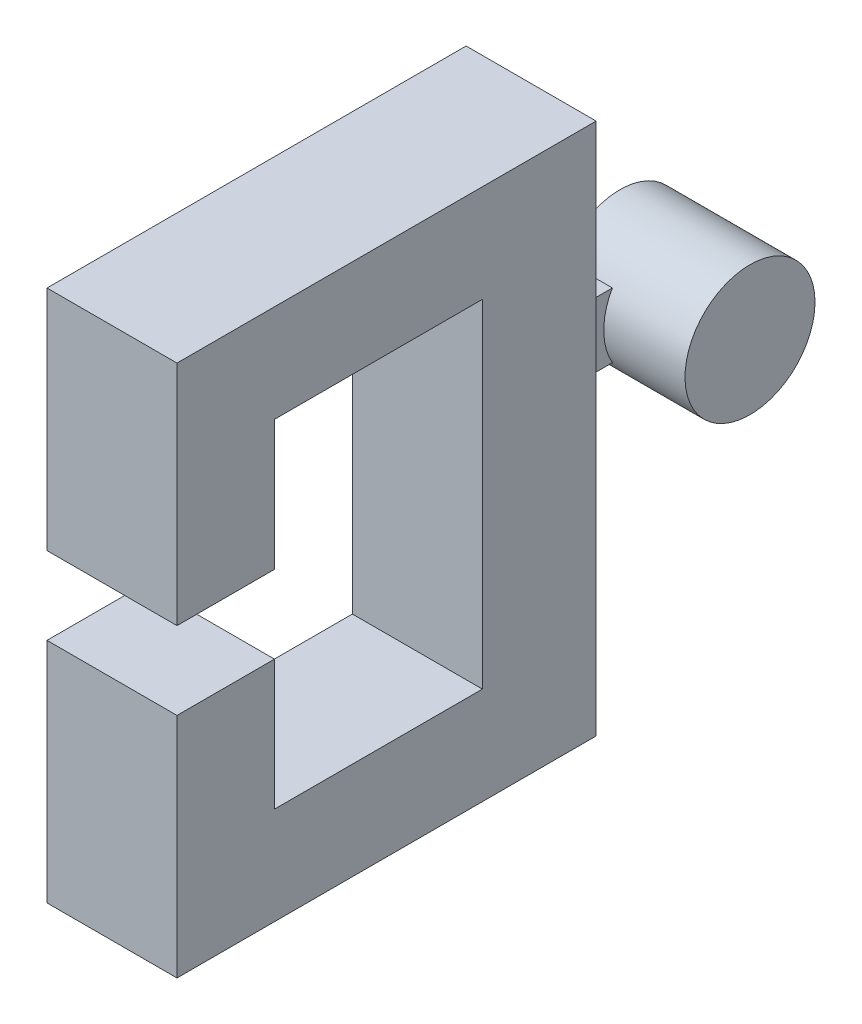
SolidWorks part; units mm, degrees
ref_plane "Front Plane" through (0, 0, 0) normal (1, 0, 0) x (0, 1, 0)
ref_plane "Top Plane" through (0, 0, 0) normal (0, 0, 1) x (0, 1, 0)
ref_plane "Right Plane" through (0, 0, 0) normal (0, 1, 0) x (-1, 0, 0)
sketch "Sketch1" plane through (0, 0, 0) normal (1, 0, 0) x (0, 1, 0)
  line L0 (0, 0) -> (44.4297, 0)
  line L2 (0, 0) -> (0, -81.8896)
  line L4 (104.0486, 0) -> (104.0486, -81.8896)
  line L5 (44.4297, 0) -> (44.4297, -19.05)
  line L6 (44.4297, -19.05) -> (19.05, -19.05)
  line L7 (19.05, -19.05) -> (19.05, -59.6646)
  line L8 (19.05, -59.6646) -> (84.9986, -59.6646)
  line L9 (84.9986, -59.6646) -> (84.9986, -19.05)
  line L10 (84.9986, -19.05) -> (59.6189, -19.05)
  line L11 (59.6189, -19.05) -> (59.6189, 0)
  line L12 (59.6189, 0) -> (104.0486, 0)
  line L13 (0, -81.8896) -> (45.6997, -81.8896)
  line L14 (45.6997, -81.8896) -> (45.6997, -100.9396)
  line L16 (58.3489, -100.9396) -> (58.3489, -81.8896)
  line L17 (58.3489, -81.8896) -> (104.0486, -81.8896)
  line L18 (45.6997, -81.8896) -> (58.3489, -81.8896) construction
  line L19 (52.0243, 4.8233) -> (52.0243, -124.1525) construction
  arc A2 (45.6997, -100.9396) -> (58.3489, -100.9396) centre (52.0243, -111.9527) ccw
  point P20 (52.0243, -59.6646)
  dimension "D1" = 81.8896
  dimension "D2" = 19.05
  dimension "D10" = 12.7
  dimension "D3" = 22.225
  dimension "D4" = 12.6492
  dimension "D5" = 25.3797
  dimension "D6" = 15.1892
  dimension "D7" = 19.05
  dimension "D8" = 19.05
  dimension "D9" = 26.6497
extrude "Boss-Extrude1" add sketch "Sketch1" along normal blind 25.4
sketch "Sketch2" plane through (25.4, 0, 0) normal (1, 0, 0) x (0, 1, 0)
  line L0 (45.6997, -81.8896) -> (58.3489, -81.8896)
  line L1 (58.3489, -81.8896) -> (58.3489, -100.9396)
  line L2 (58.3489, -100.9396) -> (45.6997, -100.9396) construction
  line L3 (45.6997, -100.9396) -> (45.6997, -81.8896)
  arc A0 (58.3489, -100.9396) -> (45.6997, -100.9396) centre (52.0243, -111.9527) ccw
  point P9 (52.0243, -111.9527)
extrude "Cut-Extrude1" cut sketch "Sketch2" against normal blind 15.875
